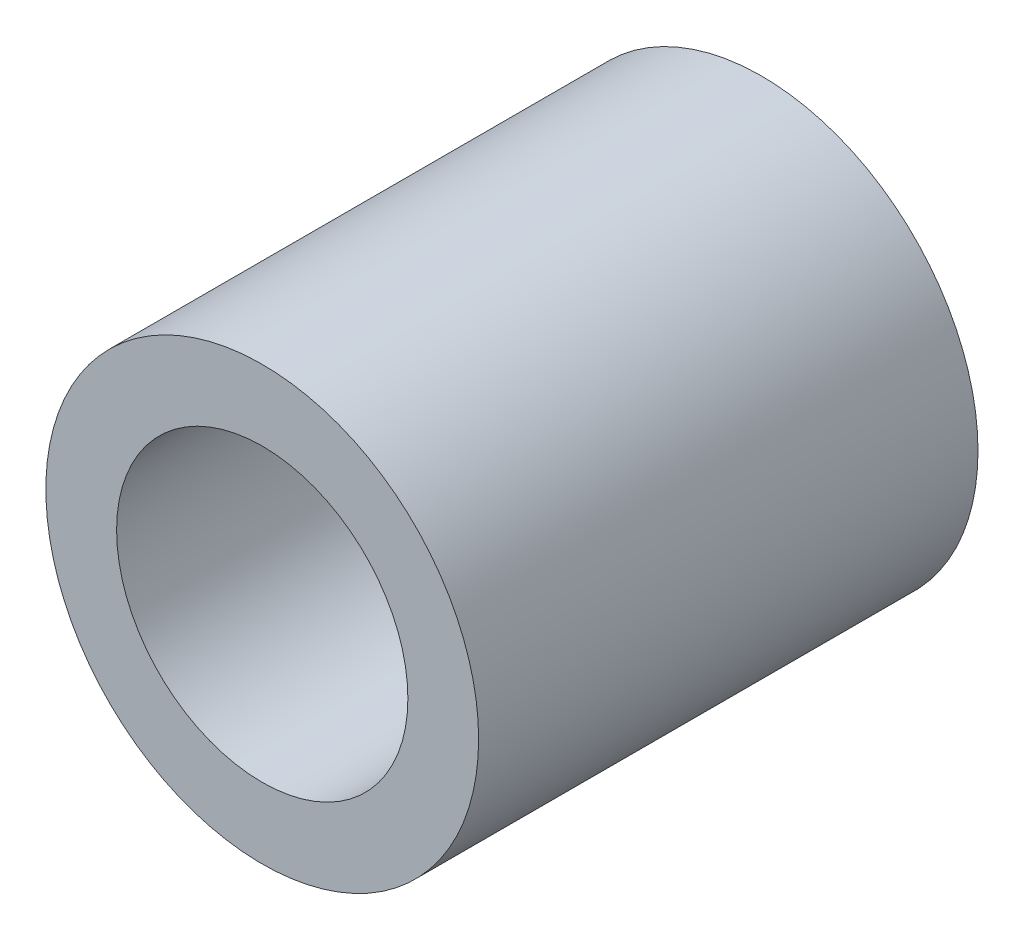
SolidWorks part; units mm, degrees
material "Latão"
ref_plane "Plano frontal" through (0, 0, 0) normal (0, 0, 1) x (1, 0, 0)
ref_plane "Plano superior" through (0, 0, 0) normal (0, 1, 0) x (1, 0, 0)
ref_plane "Plano direito" through (0, 0, 0) normal (1, 0, 0) x (0, 0, -1)
sketch "Esboço1" plane through (0, 0, 0) normal (0, 0, 1) x (1, 0, 0)
  circle A0 centre (0, 0) radius 2.6
  circle A1 centre (0, 0) radius 1.75
  dimension "D1" = 5.2
  dimension "D2" = 3.5
extrude "Ressalto-extrusão1" add sketch "Esboço1" along normal blind 6
